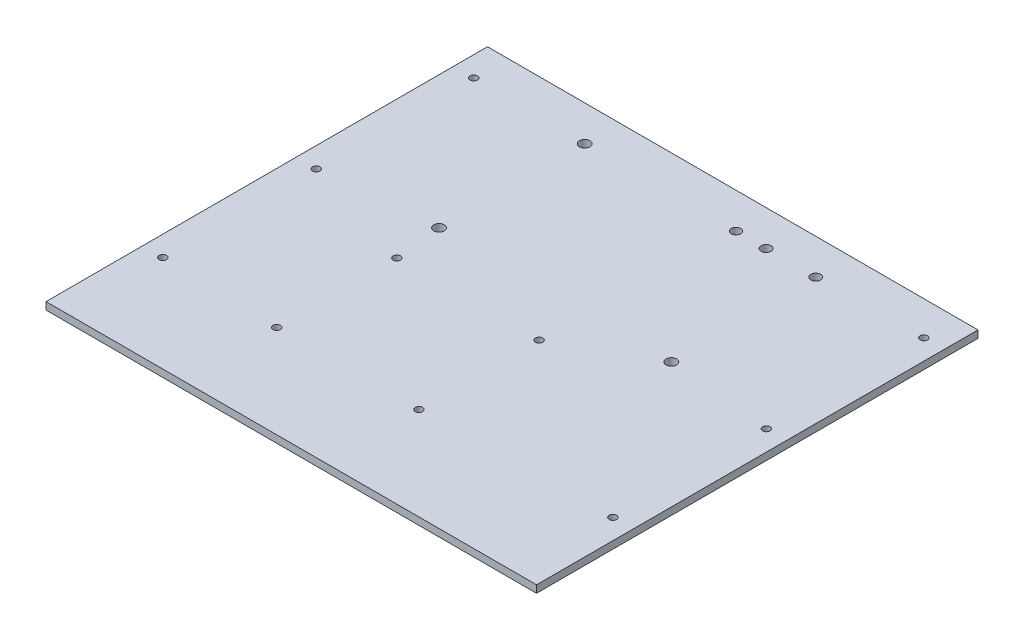
SolidWorks part; units mm, degrees
material "PMMA"
ref_plane "前视基准面" through (0, 0, 0) normal (0, 0, 1) x (1, 0, 0)
ref_plane "上视基准面" through (0, 0, 0) normal (0, 1, 0) x (1, 0, 0)
ref_plane "右视基准面" through (0, 0, 0) normal (1, 0, 0) x (0, 0, -1)
sketch "草图1" plane through (0, 0, 0) normal (0, 1, 0) x (1, 0, 0)
  line L1 (-100, 90) -> (100, 90)
  line L2 (-100, 90) -> (-100, -90)
  line L3 (-100, -90) -> (100, -90)
  line L4 (100, 90) -> (100, -90)
  line L5 (-100, 90) -> (100, -90) construction
  line L6 (-100, -90) -> (100, 90) construction
  point P0 (0, 0)
  dimension "D1" = 200
  dimension "D2" = 180
extrude "凸台-拉伸1" add sketch "草图1" along normal blind 3
sketch "草图2" plane through (0, 3, 0) normal (0, 1, 0) x (1, 0, 0)
  line L0 (0, 110.6578) -> (0, -83.5972) construction
  circle A0 centre (91.7562, 76.1634) radius 1.5
  circle A1 centre (91.7562, 11.9396) radius 1.5
  circle A2 centre (91.7562, -50.6252) radius 1.5
  circle A3 centre (-91.7562, 76.1634) radius 1.5
  circle A4 centre (-91.7562, 11.9396) radius 1.5
  circle A5 centre (-91.7562, -50.6252) radius 1.5
  dimension "D1" = 3
  dimension "D2" = 3
  dimension "D3" = 3
extrude "切除-拉伸1" cut sketch "草图2" against normal blind 3
sketch "草图3" plane through (0, 3, 0) normal (0, 1, 0) x (1, 0, 0)
  line L0 (0, 38.2795) -> (0, -90) construction
  line L1 (-100, -90) -> (100, -90) construction
  line L3 (-43.8555, -3.0835) -> (14.1445, -3.0835) construction
  line L4 (-43.8555, -3.0835) -> (-43.8555, -52.0835) construction
  line L5 (-43.8555, -52.0835) -> (14.1445, -52.0835) construction
  line L6 (14.1445, -3.0835) -> (14.1445, -52.0835) construction
  line L7 (-43.8555, -3.0835) -> (14.1445, -52.0835) construction
  line L8 (-43.8555, -52.0835) -> (14.1445, -3.0835) construction
  circle A0 centre (14.1445, -3.0835) radius 1.5
  circle A1 centre (14.1445, -52.0835) radius 1.5
  circle A2 centre (-43.8555, -52.0835) radius 1.5
  circle A3 centre (-43.8555, -3.0835) radius 1.5
  point P4 (0, -20.1238)
  dimension "D3" = 3
  dimension "D1" = 58
  dimension "D2" = 49
extrude "切除-拉伸2" cut sketch "草图3" against normal blind 3
sketch "草图4" plane through (0, 3, 0) normal (0, 1, 0) x (1, 0, 0)
  circle A0 centre (48.7944, 16.1802) radius 2.137
  circle A1 centre (48.2804, 75.5519) radius 2.0069
  circle A2 centre (28.0353, 75.5519) radius 2.0069
  circle A3 centre (15.7804, 75.5519) radius 1.9201
  circle A4 centre (-45.9295, 75.5519) radius 2.137
  circle A5 centre (-45.9295, 16.1802) radius 2.137
extrude "切除-拉伸3" cut sketch "草图4" against normal blind 3
